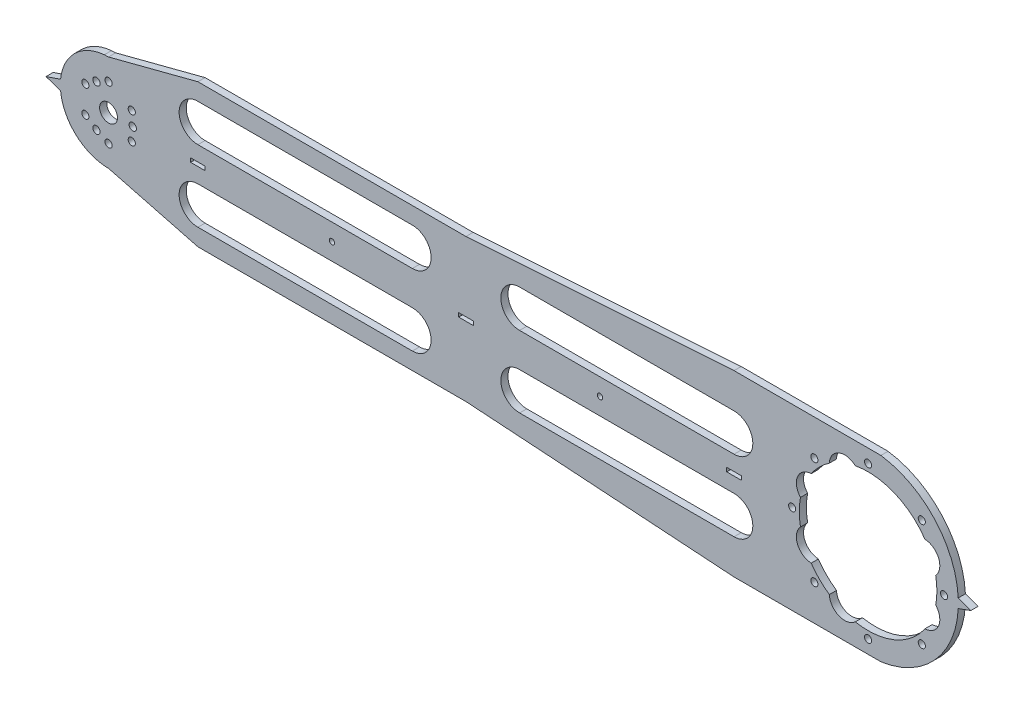
SolidWorks part; units mm, degrees
ref_plane "前视基准面" through (0, 0, 0) normal (0, 0, 1) x (1, 0, 0)
ref_plane "上视基准面" through (0, 0, 0) normal (0, 1, 0) x (1, 0, 0)
ref_plane "右视基准面" through (0, 0, 0) normal (1, 0, 0) x (0, 0, -1)
sketch "草图1" plane through (0, 0, 0) normal (0, 0, 1) x (1, 0, 0)
  line L0 (12.9904, 7.5) -> (12.9904, -7.5) construction
  line L2 (425, 0) -> (275, 0) construction
  line L3 (0, 27) -> (50, 40)
  line L4 (125, 0) -> (275, 0) construction
  line L5 (200, 0) -> (200, 4.9034) construction
  line L6 (350, 0) -> (350, 40) construction
  line L7 (195.9, -1.1) -> (204.1, -1.1)
  line L8 (195.9, -1.1) -> (195.9, 1.1)
  line L9 (195.9, 1.1) -> (204.1, 1.1)
  line L10 (204.1, -1.1) -> (204.1, 1.1)
  line L11 (195.9, -1.1) -> (204.1, 1.1) construction
  line L12 (195.9, 1.1) -> (204.1, -1.1) construction
  line L13 (54.1, 1.1) -> (45.9, 1.1)
  line L14 (54.1, 1.1) -> (54.1, -1.1)
  line L15 (54.1, -1.1) -> (45.9, -1.1)
  line L16 (45.9, 1.1) -> (45.9, -1.1)
  line L17 (54.1, 1.1) -> (45.9, -1.1) construction
  line L18 (54.1, -1.1) -> (45.9, 1.1) construction
  line L19 (354.1, 1.1) -> (345.9, 1.1)
  line L20 (354.1, 1.1) -> (354.1, -1.1)
  line L21 (354.1, -1.1) -> (345.9, -1.1)
  line L22 (345.9, 1.1) -> (345.9, -1.1)
  line L23 (354.1, 1.1) -> (345.9, -1.1) construction
  line L24 (354.1, -1.1) -> (345.9, 1.1) construction
  line L31 (350, 20) -> (50, 20) construction
  line L32 (50, 20) -> (170, 20) construction
  line L35 (50, 30.5) -> (170, 30.5)
  line L38 (50, 9.5) -> (170, 9.5)
  line L39 (350, 20) -> (230, 20) construction
  line L40 (350, 30.5) -> (230, 30.5)
  line L41 (350, 9.5) -> (230, 9.5)
  line L42 (50, -20) -> (170, -20) construction
  line L43 (50, -30.5) -> (170, -30.5)
  line L44 (50, -9.5) -> (170, -9.5)
  line L45 (350, -20) -> (230, -20) construction
  line L46 (350, -30.5) -> (230, -30.5)
  line L47 (350, -9.5) -> (230, -9.5)
  line L48 (0, 0) -> (-35, 0) construction
  line L63 (0, -27) -> (-2.3544, -26.8972)
  line L66 (-35, 0) -> (-12.9904, 7.5) construction
  line L70 (-26.857, 2.7748) -> (-35, 0)
  line L71 (-12.9904, -7.5) -> (-35, 0) construction
  line L72 (-35, 0) -> (-26.857, -2.7748)
  line L82 (0, 27) -> (-2.3544, 26.8972)
  line L87 (425, 50) -> (432.1772, 50)
  line L91 (50, 40) -> (200, 40)
  line L92 (200, 40) -> (350, 50)
  line L93 (50, -40) -> (200, -40)
  line L94 (200, -40) -> (350, -50)
  line L95 (425, -50) -> (432.1931, -49.9977)
  line L96 (467.5, 0) -> (482.5, 0)
  line L97 (482.5, 0) -> (462.8249, 7.1781) construction
  line L98 (482.5, 0) -> (475.4469, 2.5732)
  line L99 (462.8251, -7.1772) -> (482.5, 0) construction
  line L100 (475.4469, -2.5729) -> (482.5, 0)
  line L101 (0, -27) -> (50, -40)
  line L102 (350, 50) -> (425, 50)
  line L103 (350, -50) -> (425, -50)
  line L180 (742.3922, -10.8885) -> (651.0269, -10.8885) construction
  line L181 (425, 0) -> (425, 50) construction
  line L182 (425, 0) -> (473, 0) construction
  circle A0 centre (0, 0) radius 15 construction
  circle A1 centre (0, -15) radius 2
  circle A2 centre (-12.9904, -7.5) radius 2
  circle A3 centre (-12.9904, 7.5) radius 2
  circle A4 centre (0, 15) radius 2
  circle A5 centre (12.9904, 7.5) radius 2
  circle A6 centre (12.9904, -7.5) radius 2
  circle A7 centre (0, 0) radius 13.53 construction
  circle A8 centre (13.53, 0) radius 2.05
  circle A9 centre (-6.765, -11.7173) radius 2.05
  circle A10 centre (-6.765, 11.7173) radius 2.05
  circle A11 centre (0, 0) radius 27 construction
  circle A12 centre (0, 0) radius 5
  circle A13 centre (394.948, -30.052) radius 2
  circle A20 centre (382.5, 0) radius 2
  circle A26 centre (275, 0) radius 1.5
  circle A27 centre (125, 0) radius 1.5
  arc A34 (50, 30.5) -> (50, 9.5) centre (50, 20) ccw
  arc A35 (170, 9.5) -> (170, 30.5) centre (170, 20) ccw
  arc A36 (350, 30.5) -> (350, 9.5) centre (350, 20) cw
  arc A37 (230, 9.5) -> (230, 30.5) centre (230, 20) cw
  arc A38 (50, -30.5) -> (50, -9.5) centre (50, -20) cw
  arc A39 (170, -9.5) -> (170, -30.5) centre (170, -20) cw
  arc A40 (350, -30.5) -> (350, -9.5) centre (350, -20) ccw
  arc A41 (230, -9.5) -> (230, -30.5) centre (230, -20) ccw
  arc A45 (-2.3544, 26.8972) -> (-26.857, 2.7748) centre (0, 0) ccw
  arc A46 (-2.3544, -26.8972) -> (-26.857, -2.7748) centre (0, 0) cw
  circle A49 centre (467.5, 0) radius 2
  circle A50 centre (455.052, -30.052) radius 2
  circle A51 centre (455.052, 30.052) radius 2
  circle A52 centre (394.948, 30.052) radius 2
  circle A53 centre (425, 42.5026) radius 2
  arc A55 (456.8214, 21.6714) -> (462.8249, 7.1781) centre (456.4997, 13.0481) cw
  arc A56 (462.8251, -7.1772) -> (456.822, -21.6706) centre (456.5, -13.0473) cw
  arc A58 (417.8228, -37.8251) -> (403.3294, -31.822) centre (411.9527, -31.5) cw
  arc A59 (393.1786, -21.6714) -> (387.1751, -7.1781) centre (393.5003, -13.0481) cw
  arc A60 (387.1749, 7.1772) -> (393.178, 21.6706) centre (393.5, 13.0473) cw
  arc A61 (403.3286, 31.8214) -> (417.8219, 37.8249) centre (411.9519, 31.4997) cw
  arc A62 (432.1772, 37.8251) -> (417.8219, 37.8249) centre (425, 0) ccw
  arc A64 (462.8251, -7.1772) -> (462.8249, 7.1781) centre (425, 0) ccw
  arc A66 (417.8228, -37.8251) -> (432.1781, -37.8249) centre (425, 0) ccw
  arc A67 (393.1786, -21.6714) -> (403.3294, -31.822) centre (425, 0) ccw
  arc A68 (387.1749, 7.1772) -> (387.1751, -7.1781) centre (425, 0) ccw
  arc A69 (403.3286, 31.8214) -> (393.178, 21.6706) centre (425, 0) ccw
  circle A70 centre (425, 0) radius 48 construction
  circle A74 centre (425, -42.5026) radius 2
  arc A75 (432.1772, 50) -> (432.1931, -49.9977) centre (425, 0) cw construction
  arc A76 (432.1772, 37.8251) -> (456.8214, 21.6714) centre (425, 0) cw
  arc A77 (432.1781, -37.8249) -> (456.822, -21.6706) centre (425, 0) ccw
  arc A78 (475.4469, 2.5732) -> (432.1772, 50) centre (425, 0) ccw
  arc A79 (432.1931, -49.9977) -> (475.4469, -2.5729) centre (425, 0) ccw
  point P57 (50, 0)
  point P62 (350, 0)
  point P77 (110, 20)
  point P85 (290, 20)
  point P92 (110, -20)
  point P99 (290, -20)
  point P111 (-27, 0)
  dimension "D1" = 6
  dimension "D2" = 3
extrude "凸台-拉伸1" add sketch "草图1" along normal blind 4
